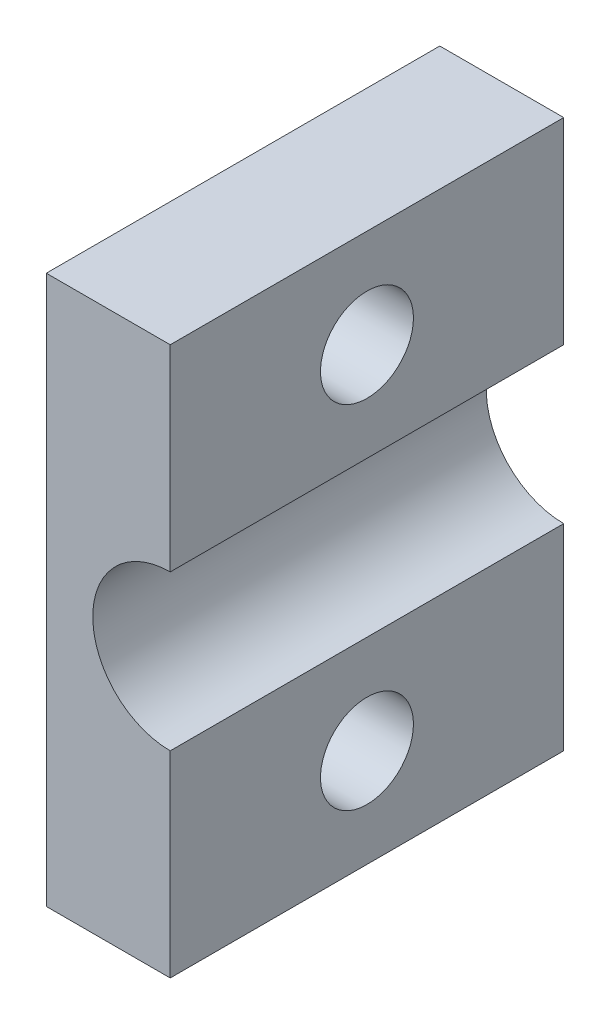
SolidWorks part; units mm, degrees
ref_plane "Front Plane" through (0, 0, 0) normal (0, 0, 1) x (1, 0, 0)
ref_plane "Top Plane" through (0, 0, 0) normal (0, 1, 0) x (1, 0, 0)
ref_plane "Right Plane" through (0, 0, 0) normal (1, 0, 0) x (0, 0, -1)
sketch "Sketch1" plane through (0, 0, 0) normal (0, 1, 0) x (1, 0, 0)
  line L0 (0, 12.7) -> (0, 0)
  line L2 (0, 0) -> (-4, 0)
  line L3 (-4, 0) -> (-4, 12.7)
  line L4 (-4, 12.7) -> (0, 12.7)
  point P2 (0, 0)
  dimension "D1" = 4
  dimension "D2" = 12.7
extrude "Boss-Extrude1" add sketch "Sketch1" along normal mid plane 17.7
sketch "Sketch2" plane through (0, 0, 0) normal (0, 0, 1) x (1, 0, 0)
  line L0 (0, 8.85) -> (0, -8.85) construction
  circle A0 centre (0, 0) radius 2.5
  dimension "D1" = 5
extrude "Cut-Extrude1" cut sketch "Sketch2" against normal through all
sketch "Sketch3" plane through (0, 0, 0) normal (1, 0, 0) x (0, 0, -1)
  line L0 (0, 2.5) -> (12.7, 2.5) construction
  line L1 (0, 8.85) -> (0, 2.5) construction
  line L4 (0, -2.5) -> (0, -8.85) construction
  circle A0 centre (6.35, 5.675) radius 1.5
  circle A1 centre (6.35, -5.675) radius 1.5
  point P6 (6.35, 2.5)
  point P7 (0, 0)
  point P10 (0, 5.675)
  point P11 (0, 0)
  point P14 (0, -5.675)
  dimension "D1" = 3
  dimension "D2" = 3
extrude "Cut-Extrude2" cut sketch "Sketch3" against normal through all
